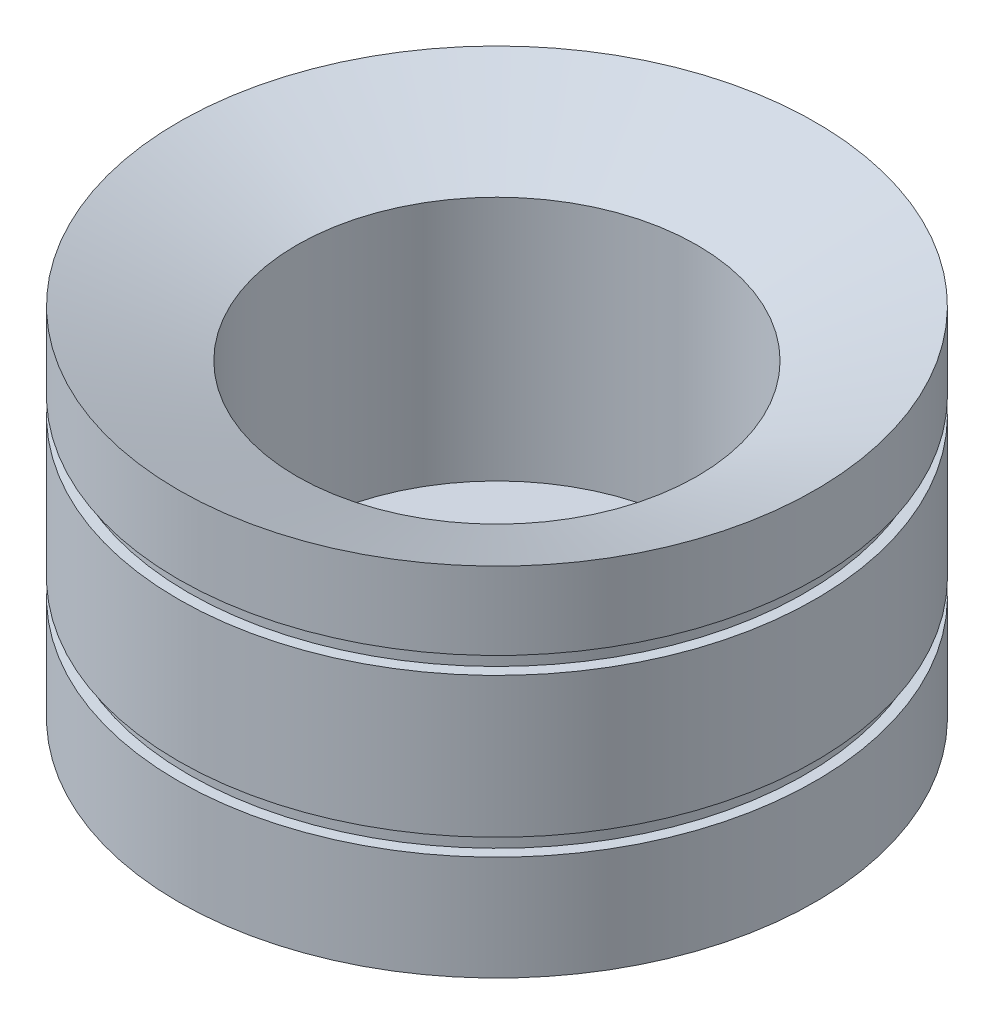
SolidWorks part; units mm, degrees
ref_plane "Front Plane" through (0, 0, 0) normal (0, 0, 1) x (1, 0, 0)
ref_plane "Top Plane" through (0, 0, 0) normal (0, 1, 0) x (1, 0, 0)
ref_plane "Right Plane" through (0, 0, 0) normal (1, 0, 0) x (0, 0, -1)
sketch "Sketch1" plane through (0, 0, 0) normal (0, 0, 1) x (1, 0, 0)
  line L0 (0, 54.3448) -> (0, -54.7264) construction
  line L1 (0, -48.662) -> (-70, -48.662)
  line L2 (-70, -48.662) -> (-70, -25.662)
  line L3 (-70, -25.662) -> (-67.76, -25.5446)
  line L4 (-67.76, -25.5446) -> (-67.76, -21.9846)
  line L5 (-67.76, -21.9846) -> (-70, -21.8672)
  line L6 (-70, -21.8672) -> (-70, 8.9359)
  line L7 (-70, 8.9359) -> (-67.7631, 9.0531)
  line L8 (-67.7631, 9.0531) -> (-67.7631, 12.6131)
  line L9 (-67.7631, 12.6131) -> (-70, 12.7303)
  line L10 (-70, 12.7303) -> (-70, 29.7303)
  line L11 (-70, 29.7303) -> (-44, 19.338)
  line L12 (-44, 19.338) -> (-44, -34.662)
  line L13 (-44, -34.662) -> (0, -34.662)
  line L14 (0, -48.662) -> (0, -34.662)
  dimension "D1" = 70
  dimension "D2" = 23
  dimension "D3" = 2.24
  dimension "D4" = 93
  dimension "D5" = 93
  dimension "D6" = 0
  dimension "D7" = 93
  dimension "D8" = 0
  dimension "D9" = 2.24
  dimension "D10" = 28
  dimension "D11" = 54
  dimension "D12" = 44
  dimension "D13" = 14
  dimension "D14" = 17
  dimension "D15" = 3.56
  dimension "D16" = 3.56
revolve "Revolve2" add sketch "Sketch1" angle 360 about L0
